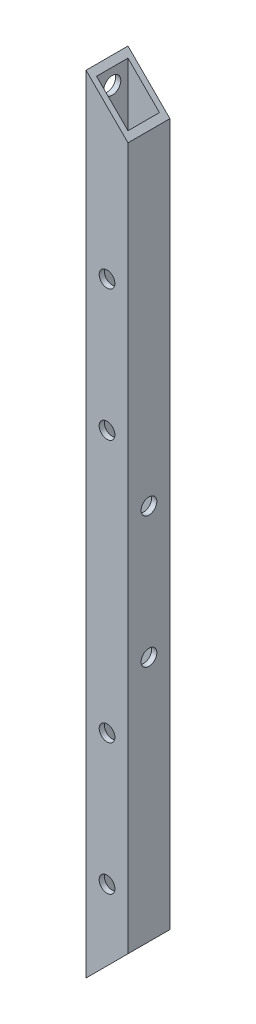
SolidWorks part; units mm, degrees
ref_plane "前视基准面" through (0, 0, 0) normal (0, 0, 1) x (1, 0, 0)
ref_plane "上视基准面" through (0, 0, 0) normal (0, 1, 0) x (1, 0, 0)
ref_plane "右视基准面" through (0, 0, 0) normal (1, 0, 0) x (0, 0, -1)
sketch "草图1" plane through (0, 0, 0) normal (0, 1, 0) x (1, 0, 0)
  line L1 (-4, 4) -> (4, 4)
  line L2 (-4, 4) -> (-4, -4)
  line L3 (-4, -4) -> (4, -4)
  line L4 (4, 4) -> (4, -4)
  line L5 (0, -4) -> (0, 4) construction
  line L6 (-4, 0) -> (4, 0) construction
  line L7 (-3, 3) -> (3, 3)
  line L8 (-3, 3) -> (-3, -3)
  line L9 (-3, -3) -> (3, -3)
  line L10 (3, 3) -> (3, -3)
  line L11 (0, -3) -> (0, 3) construction
  line L12 (-3, 0) -> (3, 0) construction
  point P0 (0, 0)
  point P4 (0, 0)
  dimension "D1" = 8
  dimension "D2" = 8
  dimension "D3" = 1
  dimension "D4" = 1
extrude "凸台-拉伸1" add sketch "草图1" along normal blind 150
sketch "草图2" plane through (4, 0, 0) normal (1, 0, 0) x (0, 0, -1)
  line L0 (0, 150) -> (0, 0) construction
  line L1 (-4, 150) -> (4, 150) construction
  circle A0 centre (0, 80) radius 1.5
  circle A1 centre (0, 55) radius 1.5
  dimension "D1" = 3
  dimension "D2" = 3
  dimension "D3" = 25
  dimension "D4" = 70
extrude "切除-拉伸1" cut sketch "草图2" against normal blind 10
sketch "草图3" plane through (0, 0, -4) normal (0, 0, -1) x (-1, 0, 0)
  line L0 (4, 150) -> (-4, 142)
  line L1 (-4, 150) -> (-4, 0) construction
  line L2 (-4, 142) -> (-4, 150)
  line L3 (-4, 150) -> (4, 150)
  line L4 (4, 0) -> (-4, 8)
  line L5 (-4, 8) -> (-4, 0)
  line L6 (-4, 0) -> (4, 0) construction
  line L7 (-4, 0) -> (4, 0)
extrude "切除-拉伸2" cut sketch "草图3" against normal blind 10
sketch "草图4" plane through (4, 0, 0) normal (1, 0, 0) x (0, 0, -1)
  line L0 (-1.5, 80) -> (1.5, 80) construction
  line L1 (-1.5, 55) -> (1.5, 55) construction
  line L2 (0, 80) -> (0, 55) construction
  line L3 (-4, 67.5) -> (4, 67.5) construction
  line L4 (-4, 142) -> (-4, 8) construction
  line L5 (4, 142) -> (4, 8) construction
  circle A0 centre (0, 80) radius 1.5 construction
  circle A1 centre (0, 55) radius 1.5 construction
sketch "草图5" plane through (0, 0, 4) normal (0, 0, 1) x (1, 0, 0)
  line L0 (0, 146) -> (0, 4) construction
  line L1 (4, 142) -> (-4, 150) construction
  line L2 (-4, 0) -> (4, 8) construction
  line L3 (4, 67.5) -> (-4, 67.5) construction
  line L4 (4, 80) -> (4, 55) construction
  line L5 (-4, 150) -> (-4, 0) construction
  circle A1 centre (0, 42.5) radius 1.5
  circle A3 centre (0, 92.5) radius 1.5
  circle A4 centre (0, 117.5) radius 1.5
  circle A6 centre (0, 17.5) radius 1.5
  point P12 (0, 67.5)
  dimension "D1" = 25
  dimension "D2" = 3
  dimension "D3" = 50
  dimension "D4" = 3
  dimension "D5" = 25
  dimension "D6" = 3
extrude "切除-拉伸3" cut sketch "草图5" against normal blind 10
sketch "草图6" plane through (-3, 0, 0) normal (1, 0, 0) x (0, 0, -1)
  line L0 (0, 0) -> (0, 150) construction
  line L1 (4, 0) -> (-4, 0) construction
  line L2 (4, 150) -> (-4, 150) construction
  circle A0 centre (0, 146) radius 1.625
  circle A1 centre (0, 4) radius 1.625
  dimension "D1" = 3.25
  dimension "D2" = 4
  dimension "D3" = 3.25
  dimension "D4" = 4
extrude "切除-拉伸4" cut sketch "草图6" against normal blind 10
